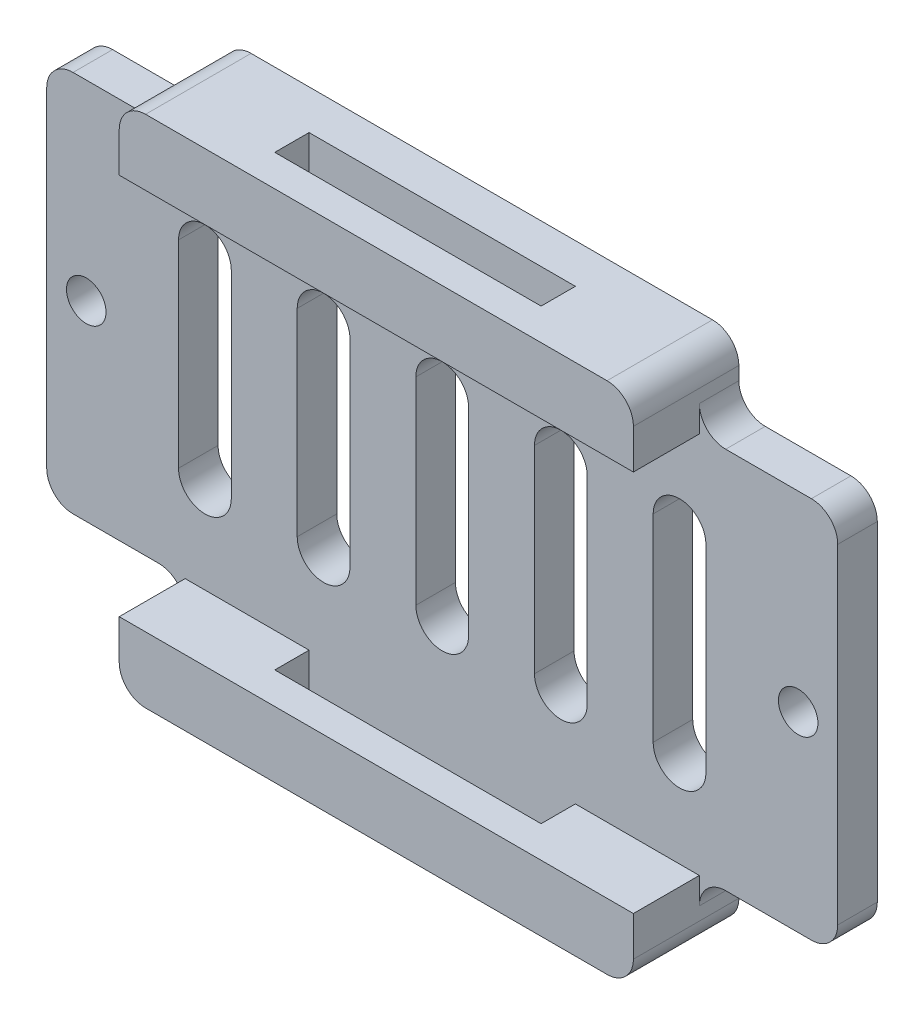
SolidWorks part; units mm, degrees
ref_plane "前视基准面" through (0, 0, 0) normal (0, 0, 1) x (1, 0, 0)
ref_plane "上视基准面" through (0, 0, 0) normal (0, 1, 0) x (1, 0, 0)
ref_plane "右视基准面" through (0, 0, 0) normal (1, 0, 0) x (0, 0, -1)
other "Configuration Table"
sketch "草图2" plane through (0, 0, 0) normal (0, 0, 1) x (1, 0, 0)
  line L1 (19.5, -2.5) -> (-19.5, -2.5)
  line L2 (19.5, -2.5) -> (19.5, 2.5)
  line L3 (19.5, 2.5) -> (-19.5, 2.5)
  line L4 (-19.5, -2.5) -> (-19.5, 2.5)
  line L5 (19.5, -2.5) -> (-19.5, 2.5) construction
  line L6 (19.5, 2.5) -> (-19.5, -2.5) construction
  point P0 (0, 0)
  dimension "D1" = 39
  dimension "D2" = 5
extrude "凸台-拉伸1" add sketch "草图2" along normal blind 8
sketch "草图3" plane through (0, 2.5, 0) normal (0, 1, 0) x (1, 0, 0)
  line L5 (-30, 0) -> (30, 0)
  line L6 (30, 0) -> (30, -3)
  line L7 (30, -3) -> (-30, -3)
  line L8 (-30, -3) -> (-30, 0)
  line L9 (0, 0) -> (0, -8) construction
  line L10 (19.5, -8) -> (-19.5, -8) construction
  dimension "D1" = 3
  dimension "D2" = 60
  dimension "D3" = 30
extrude "凸台-拉伸2" add sketch "草图3" along normal blind 29
sketch "草图4" plane through (0, -2.5, 0) normal (0, -1, 0) x (1, 0, 0)
  line L0 (-19.5, 5.6) -> (19.5, 5.6) construction
  line L1 (-19.5, 8) -> (-19.5, 0) construction
  line L2 (19.5, 8) -> (19.5, 0) construction
  line L3 (-19.5, 8) -> (19.5, 8) construction
  line L4 (0, 8) -> (0, 0) construction
  line L6 (10.1, 3) -> (-10.1, 3)
  line L7 (10.1, 3) -> (10.1, 5.6)
  line L8 (10.1, 5.6) -> (-10.1, 5.6)
  line L9 (-10.1, 3) -> (-10.1, 5.6)
  line L10 (10.1, 3) -> (-10.1, 5.6) construction
  line L11 (10.1, 5.6) -> (-10.1, 3) construction
  point P11 (0, 4.3)
  dimension "D1" = 2.4
  dimension "D2" = 20.2
  dimension "D3" = 2.6
extrude "切除-拉伸1" cut sketch "草图4" against normal through all
sketch "草图5" plane through (0, 0, 0) normal (0, 0, -1) x (-1, 0, 0)
  line L0 (0, 31.5) -> (0, -2.5) construction
  line L1 (-30, 31.5) -> (30, 31.5) construction
  line L2 (19.5, -2.5) -> (-19.5, -2.5) construction
  line L3 (-30, 2.5) -> (-19.5, 2.5) construction
  circle A0 centre (-27, 17) radius 1.5
  circle A1 centre (27, 17) radius 1.5
  dimension "D1" = 3
  dimension "D2" = 27
  dimension "D3" = 14.5
extrude "切除-拉伸2" cut sketch "草图5" against normal blind 10
fillet "圆角1" radius 2 6 edges at (-30, 31.5, 1.5) (-30, 2.5, 1.5) (30, 31.5, 1.5) (30, 2.5, 1.5) (19.5, -2.5, 4) (-19.5, -2.5, 4)
fillet "圆角2" radius 2 2 edges at (19.5, 2.5, 1.5) (-19.5, 2.5, 1.5)
sketch "草图6" plane through (0, 31.5, 0) normal (0, 1, 0) x (1, 0, 0)
  line L0 (0, 0) -> (0, -3) construction
  line L1 (-28, -3) -> (28, -3) construction
  line L3 (19.5, -3) -> (-19.5, -3)
  line L4 (19.5, -3) -> (19.5, 0)
  line L5 (19.5, 0) -> (-19.5, 0)
  line L6 (-19.5, -3) -> (-19.5, 0)
  line L7 (19.5, -3) -> (-19.5, 0) construction
  line L8 (19.5, 0) -> (-19.5, -3) construction
  point P5 (0, -1.5)
extrude "凸台-拉伸3" add sketch "草图6" along normal blind 5
sketch "草图7" plane through (0, 0, 3) normal (0, 0, 1) x (1, 0, 0)
  line L1 (-19.5, 36.5) -> (19.5, 36.5)
  line L2 (-19.5, 36.5) -> (-19.5, 31.5)
  line L3 (-19.5, 31.5) -> (19.5, 31.5)
  line L4 (19.5, 36.5) -> (19.5, 31.5)
extrude "凸台-拉伸4" add sketch "草图7" along normal up to surface (5 mm away) up to face at (0, -0.3047, 8)
sketch "草图8" plane through (0, 36.5, 0) normal (0, 1, 0) x (1, 0, 0)
  line L0 (0, 0) -> (0, -8) construction
  line L1 (19.5, -8) -> (-19.5, -8) construction
  line L3 (10.1, -5.6) -> (-10.1, -5.6)
  line L4 (10.1, -5.6) -> (10.1, -3)
  line L5 (10.1, -3) -> (-10.1, -3)
  line L6 (-10.1, -5.6) -> (-10.1, -3)
  line L7 (10.1, -5.6) -> (-10.1, -3) construction
  line L8 (10.1, -3) -> (-10.1, -5.6) construction
  point P5 (0, -4.3)
  dimension "D1" = 2.4
  dimension "D2" = 20.2
  dimension "D3" = 2.6
extrude "切除-拉伸3" cut sketch "草图8" against normal blind 5
fillet "圆角3" radius 2 4 edges at (19.5, 31.5, 1.5) (19.5, 36.5, 4) (-19.5, 36.5, 4) (-19.5, 31.5, 1.5)
sketch "草图9" plane through (0, 0, 0) normal (0, 0, -1) x (-1, 0, 0)
  line L0 (-30, 17) -> (30, 17) construction
  line L1 (-30, 29.5) -> (-30, 4.5) construction
  line L2 (30, 29.5) -> (30, 4.5) construction
  line L3 (0, 36.5) -> (0, -2.5) construction
  line L4 (-17.5, 36.5) -> (17.5, 36.5) construction
  line L5 (17.5, -2.5) -> (-17.5, -2.5) construction
  line L6 (0, 24.5) -> (0, 9.5) construction
  line L7 (2, 24.5) -> (2, 9.5)
  line L8 (-2, 24.5) -> (-2, 9.5)
  line L9 (7, 24.5) -> (7, 9.5)
  line L10 (11, 24.5) -> (11, 9.5)
  line L11 (9, 24.5) -> (9, 9.5) construction
  line L12 (16, 24.5) -> (16, 9.5)
  line L13 (20, 24.5) -> (20, 9.5)
  line L14 (18, 24.5) -> (18, 9.5) construction
  line L15 (-11, 24.5) -> (-11, 9.5)
  line L16 (-7, 24.5) -> (-7, 9.5)
  line L17 (-9, 24.5) -> (-9, 9.5) construction
  line L18 (-20, 24.5) -> (-20, 9.5)
  line L19 (-16, 24.5) -> (-16, 9.5)
  line L20 (-18, 24.5) -> (-18, 9.5) construction
  arc A0 (2, 24.5) -> (-2, 24.5) centre (0, 24.5) ccw
  arc A1 (-2, 9.5) -> (2, 9.5) centre (0, 9.5) ccw
  arc A2 (11, 24.5) -> (7, 24.5) centre (9, 24.5) ccw
  arc A3 (7, 9.5) -> (11, 9.5) centre (9, 9.5) ccw
  arc A4 (20, 24.5) -> (16, 24.5) centre (18, 24.5) ccw
  arc A5 (16, 9.5) -> (20, 9.5) centre (18, 9.5) ccw
  arc A6 (-7, 24.5) -> (-11, 24.5) centre (-9, 24.5) ccw
  arc A7 (-11, 9.5) -> (-7, 9.5) centre (-9, 9.5) ccw
  arc A8 (-16, 24.5) -> (-20, 24.5) centre (-18, 24.5) ccw
  arc A9 (-20, 9.5) -> (-16, 9.5) centre (-18, 9.5) ccw
  point P14 (0, 17)
  point P23 (9, 17)
  point P30 (18, 17)
  point P36 (-9, 17)
  point P43 (-18, 17)
  dimension "D3" = 2
  dimension "D1" = 0
  dimension "D2" = 15
  dimension "D4" = 3
  dimension "D5" = 3
extrude "切除-拉伸4" cut sketch "草图9" against normal blind 5
